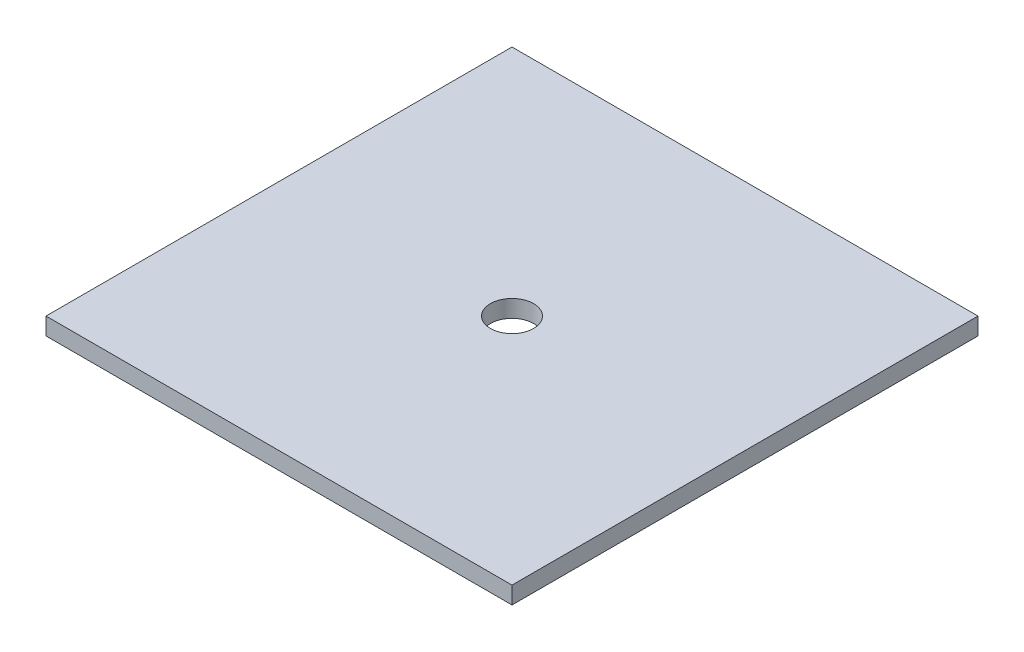
SolidWorks part; units mm, degrees
ref_plane "Plano frontal" through (0, 0, 0) normal (0, 0, 1) x (1, 0, 0)
ref_plane "Plano superior" through (0, 0, 0) normal (0, 1, 0) x (1, 0, 0)
ref_plane "Plano direito" through (0, 0, 0) normal (1, 0, 0) x (0, 0, -1)
sketch "Esboço2" plane through (0, 0, 0) normal (0, 1, 0) x (1, 0, 0)
  line L1 (75, -87) -> (-87, -87)
  line L2 (75, -87) -> (75, 75)
  line L3 (75, 75) -> (-87, 75)
  line L4 (-87, -87) -> (-87, 75)
  line L5 (75, -87) -> (-87, 75) construction
  line L6 (75, 75) -> (-87, -87) construction
  point P0 (-6, -6)
  dimension "D1" = 162
  dimension "D2" = 162
extrude "Ressalto-extrusão2" add sketch "Esboço2" along normal blind 6
sketch "Esboço3" plane through (0, 6, 0) normal (0, 1, 0) x (1, 0, 0)
  circle A0 centre (-6, -6) radius 7.5
  point P14 (-4.6601, -6)
  point P15 (-6, -6)
  dimension "D1" = 15
extrude "Corte-extrusão1" cut sketch "Esboço3" against normal through all
